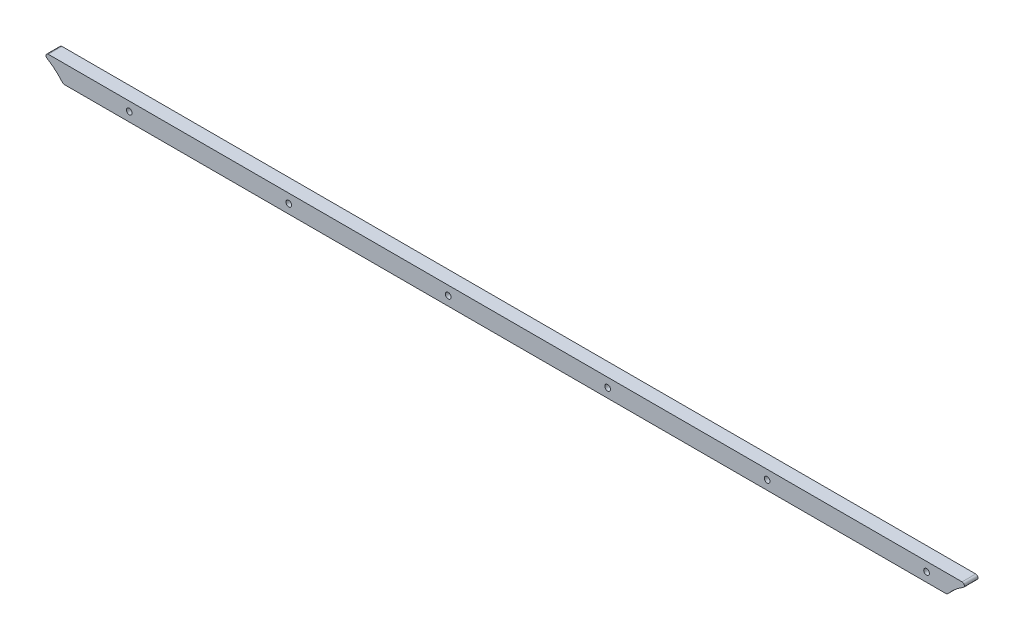
SolidWorks part; units mm, degrees
ref_plane "Ebene vorne" through (0, 0, 0) normal (0, 0, 1) x (1, 0, 0)
ref_plane "Ebene oben" through (0, 0, 0) normal (0, 1, 0) x (1, 0, 0)
ref_plane "Ebene rechts" through (0, 0, 0) normal (1, 0, 0) x (0, 0, -1)
sketch "Skizze1" plane through (0, 0, 0) normal (0, 0, 1) x (1, 0, 0)
  line L6 (225, 17) -> (409.0238, 17) construction
  line L7 (0, 25) -> (450, 25) construction
  line L8 (225, 17) -> (20.9762, 17) construction
  line L9 (225, 17) -> (409.0238, 17)
  line L10 (10.198, 25) -> (419.802, 25)
  line L11 (225, 17) -> (20.9762, 17)
  arc A2 (419.802, 25) -> (409.0238, 17) centre (430, 0) ccw construction
  arc A3 (20.9762, 17) -> (10.198, 25) centre (0, 0) ccw construction
  arc A4 (419.802, 25) -> (409.0238, 17) centre (430, 0) ccw
  arc A5 (20.9762, 17) -> (10.198, 25) centre (0, 0) ccw
extrude "Aufsatz-Linear austragen1" add sketch "Skizze1" against normal up to vertex (8.5 mm away) from vertex at -2.5
fillet "Verrundung1" radius 1 4 edges at (419.802, 25, -5.5) (409.0238, 17, -5.5) (20.9762, 17, -5.5) (10.198, 25, -5.5)
sketch "Skizze2" plane through (0, 0, -2.5) normal (0, 0, 1) x (1, 0, 0)
  point P6 (400, 21)
  point P8 (330, 21)
  point P10 (260, 21)
  point P12 (190, 21)
  point P14 (120, 21)
  point P16 (50, 21)
hole_wizard "Ø2.5 (2.5) Durchmesser Bohrung1" positions "Skizze2" profile "Skizze3" hole size "Ø2.5" standard "DIN" end condition up to next
sketch "Skizze3" plane through (400, 21, -2.5) normal (1, 0, 0) x (0, -1, 0)
  line L0 (0, 0) -> (0, 6)
  line L1 (0, 6) -> (1.25, 6)
  line L2 (1.25, 6) -> (1.25, 0)
  line L5 (1.25, 0) -> (0, 0)
  line L11 (0, -6.35) -> (0, 107.95) construction
  dimension "Bohrerdurchmesser" = 2.5
  dimension "Bohrungstiefe" = 6
